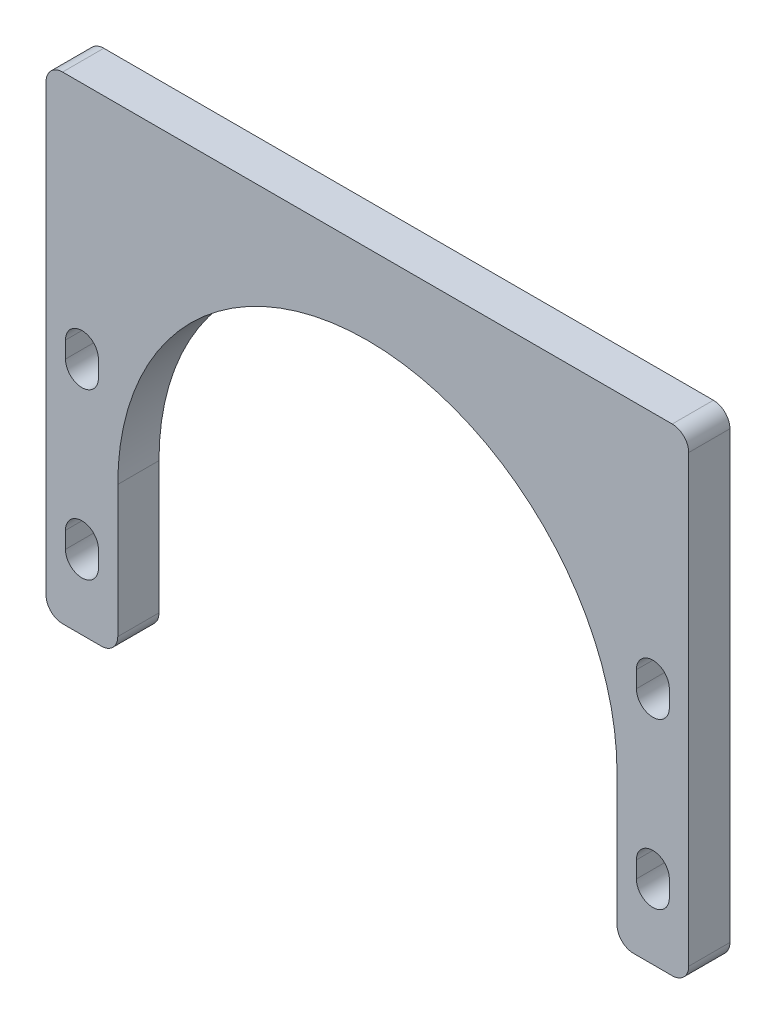
SolidWorks part; units mm, degrees
ref_plane "前视基准面" through (0, 0, 0) normal (0, 0, 1) x (1, 0, 0)
ref_plane "上视基准面" through (0, 0, 0) normal (0, 1, 0) x (1, 0, 0)
ref_plane "右视基准面" through (0, 0, 0) normal (1, 0, 0) x (0, 0, -1)
sketch "草图1" plane through (0, 0, 0) normal (0, 0, 1) x (1, 0, 0)
  line L0 (0, 60.5413) -> (0, -56.4587) construction
  line L1 (-39, 40) -> (39, 40)
  line L2 (-39, 0) -> (-30.3, 0)
  line L3 (-39, 40) -> (-39, -18)
  line L4 (-30.3, 0) -> (-30.3, -18)
  line L5 (-30.3, -18) -> (-39, -18)
  line L6 (-34.65, -18) -> (-34.65, 17.9881) construction
  line L7 (39, 40) -> (39, -18)
  line L8 (30.3, -18) -> (39, -18)
  line L9 (30.3, 0) -> (30.3, -18)
  line L10 (30.3, 0) -> (39, 0)
  arc A0 (30.3, 0) -> (-30.3, 0) centre (0, 0) ccw
  circle A1 centre (-34.65, 10) radius 2
  circle A2 centre (-34.65, -10) radius 2
  circle A3 centre (34.65, -10) radius 2
  circle A4 centre (34.65, 10) radius 2
  point P7 (0, 40)
  dimension "D1" = 78
  dimension "D2" = 60.6
  dimension "D3" = 20
  dimension "D4" = 40
  dimension "D5" = 8
extrude "凸台-拉伸1" add sketch "草图1" along normal blind 5 contours A0 L10 L7 L1 L3 L2 A1 A4 | L5 L4 L2 L3 A2 | L10 L9 L8 L7 A3
fillet "圆角1" radius 2 6 edges at (-30.3, -18, 2.5) (-39, -18, 2.5) (30.3, -18, 2.5) (39, -18, 2.5) (39, 40, 2.5) (-39, 40, 2.5)
sketch "草图2" plane through (0, 0, 5) normal (0, 0, 1) x (1, 0, 0)
  line L0 (-36.65, 10) -> (-36.65, 12)
  line L1 (-32.65, 10) -> (-32.65, 12)
  line L2 (-34.65, 10) -> (-34.65, 27.2711) construction
  line L3 (-36.65, -10) -> (-36.65, -8)
  line L4 (-32.65, -10) -> (-32.65, -8)
  line L5 (-34.65, -10) -> (-34.65, 0) construction
  line L6 (-36.65, 10) -> (-32.65, 10)
  line L7 (-36.65, -10) -> (-32.65, -10)
  circle A0 centre (-34.65, 10) radius 2 construction
  circle A4 centre (-34.65, -10) radius 2 construction
  arc A5 (-32.65, 12) -> (-36.65, 12) centre (-34.65, 12) ccw
  arc A7 (-32.65, -8) -> (-36.65, -8) centre (-34.65, -8) ccw
  dimension "D2" = 2
  dimension "D4" = 2
extrude "切除-拉伸1" cut sketch "草图2" against normal up to next
mirror "镜向1" about plane through (0, 0, 0) normal (1, 0, 0) of "切除-拉伸1"
